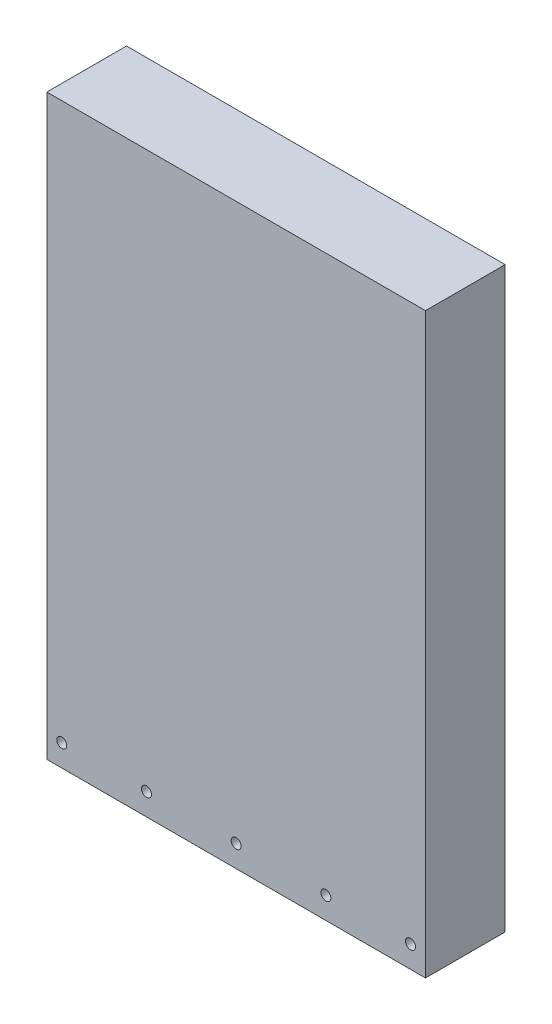
SolidWorks part; units mm, degrees
ref_plane "Plano frontal" through (0, 0, 0) normal (0, 0, 1) x (1, 0, 0)
ref_plane "Plano superior" through (0, 0, 0) normal (0, 1, 0) x (1, 0, 0)
ref_plane "Plano direito" through (0, 0, 0) normal (1, 0, 0) x (0, 0, -1)
sketch "Esboço1" plane through (0, 0, 0) normal (0, 0, 1) x (1, 0, 0)
  line L1 (0, 0) -> (190, 0)
  line L2 (0, 0) -> (0, 290)
  line L3 (0, 290) -> (190, 290)
  line L4 (190, 0) -> (190, 290)
  line L5 (5, 285) -> (185, 285)
  line L6 (5, 285) -> (5, 5)
  line L7 (5, 5) -> (185, 5)
  line L8 (185, 285) -> (185, 5)
  point P11 (-15.4865, 377.0233)
  dimension "D1" = 290
  dimension "D2" = 190
  dimension "D3" = 5
  dimension "D4" = 5
  dimension "D5" = 5
  dimension "D6" = 5
extrude "Ressalto-extrusão1" add sketch "Esboço1" along normal blind 40
sketch "Esboço2" plane through (0, 0, 40) normal (0, 0, 1) x (1, 0, 0)
  line L1 (5, 285) -> (185, 285)
  line L2 (5, 285) -> (5, 5)
  line L3 (5, 5) -> (185, 5)
  line L4 (185, 285) -> (185, 5)
extrude "Ressalto-extrusão2" add sketch "Esboço2" against normal blind 25
sketch "Esboço4" plane through (0, 0, 15) normal (0, 0, -1) x (-1, 0, 0)
  line L0 (-5, 5) -> (-185, 5) construction
  line L1 (-185, 5) -> (-175, 5)
  line L2 (-185, 5) -> (-185, 35)
  line L4 (-175, 5) -> (-175, 34.1716)
  line L6 (-150, 34.1716) -> (-150, 5)
  line L7 (-150, 5) -> (-130, 5)
  line L8 (-130, 34.1716) -> (-130, 5)
  line L9 (-5, 5) -> (-185, 5) construction
  line L11 (-105, 34.1716) -> (-105, 5)
  line L12 (-105, 5) -> (-85, 5)
  line L13 (-85, 34.1716) -> (-85, 5)
  line L15 (-60, 34.1716) -> (-60, 5)
  line L16 (-60, 5) -> (-40, 5)
  line L17 (-40, 34.1716) -> (-40, 5)
  line L18 (-5, 285) -> (-5, 5) construction
  line L20 (-5, 35) -> (-5, 5)
  line L21 (-5, 5) -> (-15, 5)
  line L22 (-15, 34.1716) -> (-15, 5)
  line L23 (-185, 35) -> (-185, 45)
  line L24 (-185, 5) -> (-185, 285) construction
  line L25 (-185, 45) -> (-175.5858, 35.5858)
  line L26 (-149.4142, 35.5858) -> (-141.4142, 43.5858)
  line L27 (-138.5858, 43.5858) -> (-130.5858, 35.5858)
  line L28 (-104.4142, 35.5858) -> (-96.4142, 43.5858)
  line L29 (-93.5858, 43.5858) -> (-85.5858, 35.5858)
  line L30 (-59.4142, 35.5858) -> (-51.4142, 43.5858)
  line L31 (-48.5858, 43.5858) -> (-40.5858, 35.5858)
  line L32 (-14.4142, 35.5858) -> (-5, 45)
  line L33 (-5, 45) -> (-5, 35)
  arc A0 (-175.5858, 35.5858) -> (-175, 34.1716) centre (-177, 34.1716) cw
  arc A1 (-149.4142, 35.5858) -> (-150, 34.1716) centre (-148, 34.1716) ccw
  arc A2 (-130.5858, 35.5858) -> (-130, 34.1716) centre (-132, 34.1716) cw
  arc A3 (-104.4142, 35.5858) -> (-105, 34.1716) centre (-103, 34.1716) ccw
  arc A4 (-85.5858, 35.5858) -> (-85, 34.1716) centre (-87, 34.1716) cw
  arc A5 (-59.4142, 35.5858) -> (-60, 34.1716) centre (-58, 34.1716) ccw
  arc A6 (-40.5858, 35.5858) -> (-40, 34.1716) centre (-42, 34.1716) cw
  arc A7 (-14.4142, 35.5858) -> (-15, 34.1716) centre (-13, 34.1716) ccw
  arc A8 (-51.4142, 43.5858) -> (-48.5858, 43.5858) centre (-50, 42.1716) cw
  arc A9 (-96.4142, 43.5858) -> (-93.5858, 43.5858) centre (-95, 42.1716) cw
  arc A10 (-141.4142, 43.5858) -> (-138.5858, 43.5858) centre (-140, 42.1716) cw
  point P27 (-140, 5)
  point P35 (-95, 5)
  point P36 (-50, 5)
  point P39 (-175, 35)
  point P42 (-150, 35)
  point P45 (-130, 35)
  point P48 (-105, 35)
  point P53 (-60, 35)
  point P58 (-15, 35)
  point P61 (-50, 45)
  point P64 (-95, 45)
  point P67 (-140, 45)
  dimension "D7" = 2
  dimension "D2" = 10
  dimension "D3" = 25
  dimension "D4" = 25
  dimension "D5" = 25
  dimension "D6" = 25
  dimension "D8" = 30
  dimension "D9" = 30
  dimension "D10" = 30
  dimension "D11" = 10
  dimension "D12" = 10
  dimension "D13" = 10
  dimension "D14" = 10
  dimension "D15" = 10
  dimension "D16" = 20
  dimension "D17" = 20
  dimension "D18" = 20
  dimension "D19" = 10
  dimension "D20" = 40
extrude "Ressalto-extrusão3" add sketch "Esboço4" along normal blind 15
sketch "Esboço5" plane through (0, 0, 0) normal (0, 0, -1) x (-1, 0, 0)
  line L0 (-185, 180) -> (-5, 180) construction
  line L1 (-185, 45) -> (-185, 285) construction
  line L2 (-5, 285) -> (-5, 45) construction
  line L3 (-185, 60) -> (-5, 60) construction
  line L4 (-185, 165) -> (-5, 165) construction
  line L5 (-5, 150) -> (-185, 150) construction
  line L6 (-185, 135) -> (-5, 135) construction
  line L7 (-185, 45) -> (-185, 285) construction
  line L8 (-5, 120) -> (-185.0319, 120) construction
  line L9 (-185, 105) -> (-5, 105) construction
  line L10 (-5, 90) -> (-185, 90) construction
  line L11 (-185, 75) -> (-5, 75) construction
  line L12 (-185, 195) -> (-5, 195) construction
  line L13 (-5, 210) -> (-185, 210) construction
  line L14 (-185, 225) -> (-5, 225) construction
  line L15 (-185, 240) -> (-5, 240) construction
  line L16 (-5, 255) -> (-185, 255) construction
  line L17 (-185, 270) -> (-5, 270) construction
  line L18 (-95, 270) -> (-95, 60) construction
  line L19 (-77, 60) -> (-77, 270) construction
  line L20 (-59, 270) -> (-59, 60) construction
  line L21 (-41, 270) -> (-41, 60) construction
  line L22 (-23, 270) -> (-23, 60) construction
  line L23 (-113, 60) -> (-113, 270) construction
  line L24 (-131, 270) -> (-131, 60) construction
  line L25 (-149, 60) -> (-149, 270) construction
  line L26 (-167, 270) -> (-167, 60) construction
  circle A0 centre (-167, 270) radius 0.75
  circle A1 centre (-131, 270) radius 0.75
  circle A2 centre (-95, 270) radius 0.75
  circle A3 centre (-59, 270) radius 0.75
  circle A4 centre (-23, 270) radius 0.75
  circle A5 centre (-41, 255) radius 0.75
  circle A6 centre (-77, 255) radius 0.75
  circle A7 centre (-113, 255) radius 0.75
  circle A8 centre (-149, 255) radius 0.75
  circle A9 centre (-167, 240) radius 0.75
  circle A10 centre (-131, 240) radius 0.75
  circle A11 centre (-95, 240) radius 0.75
  circle A12 centre (-59, 240) radius 0.75
  circle A13 centre (-23, 240) radius 0.75
  circle A14 centre (-149, 225) radius 0.75
  circle A15 centre (-113, 225) radius 0.75
  circle A16 centre (-77, 225) radius 0.75
  circle A17 centre (-41, 225) radius 0.75
  circle A18 centre (-167, 210) radius 0.75
  circle A19 centre (-131, 210) radius 0.75
  circle A20 centre (-95, 210) radius 0.75
  circle A21 centre (-59, 210) radius 0.75
  circle A22 centre (-23, 210) radius 0.75
  circle A23 centre (-149, 195) radius 0.75
  circle A24 centre (-113, 195) radius 0.75
  circle A25 centre (-77, 195) radius 0.75
  circle A26 centre (-41, 195) radius 0.75
  circle A28 centre (-23, 180) radius 0.75
  circle A29 centre (-59, 180) radius 0.75
  circle A30 centre (-95, 180) radius 0.75
  circle A31 centre (-131, 180) radius 0.75
  circle A32 centre (-167, 180) radius 0.75
  circle A33 centre (-149, 165) radius 0.75
  circle A34 centre (-113, 165) radius 0.75
  circle A35 centre (-77, 165) radius 0.75
  circle A36 centre (-41, 165) radius 0.75
  circle A38 centre (-23, 150) radius 0.75
  circle A39 centre (-59, 150) radius 0.75
  circle A40 centre (-95, 150) radius 0.75
  circle A41 centre (-131, 150) radius 0.75
  circle A43 centre (-167, 150) radius 0.75
  circle A44 centre (-149, 135) radius 0.75
  circle A45 centre (-113, 135) radius 0.75
  circle A46 centre (-77, 135) radius 0.75
  circle A47 centre (-41, 135) radius 0.75
  circle A48 centre (-167, 120) radius 0.75
  circle A49 centre (-131, 120) radius 0.75
  circle A50 centre (-95.0159, 120) radius 0.75
  circle A51 centre (-59, 120) radius 0.75
  circle A52 centre (-23, 120) radius 0.75
  circle A53 centre (-41, 105) radius 0.75
  circle A54 centre (-77, 105) radius 0.75
  circle A55 centre (-113, 105) radius 0.75
  circle A56 centre (-149, 105) radius 0.75
  circle A57 centre (-167, 90) radius 0.75
  circle A58 centre (-149, 75) radius 0.75
  circle A59 centre (-131, 90) radius 0.75
  circle A60 centre (-113, 75) radius 0.75
  circle A61 centre (-95, 90) radius 0.75
  circle A62 centre (-77, 75) radius 0.75
  circle A63 centre (-59, 90) radius 0.75
  circle A64 centre (-41, 75) radius 0.75
  circle A65 centre (-23, 90) radius 0.75
  circle A66 centre (-23, 60) radius 0.75
  circle A68 centre (-59, 60) radius 0.75
  circle A69 centre (-95, 60) radius 0.75
  circle A70 centre (-131, 60) radius 0.75
  circle A71 centre (-167, 60) radius 0.75
  dimension "D25" = 1.5
  dimension "D1" = 15
  dimension "D2" = 15
  dimension "D3" = 15
  dimension "D4" = 15
  dimension "D5" = 15
  dimension "D6" = 15
  dimension "D7" = 15
  dimension "D8" = 15
  dimension "D9" = 15
  dimension "D10" = 15
  dimension "D11" = 15
  dimension "D12" = 15
  dimension "D13" = 15
  dimension "D14" = 15
  dimension "D15" = 15
  dimension "D16" = 18
  dimension "D17" = 18
  dimension "D18" = 18
  dimension "D19" = 18
  dimension "D20" = 18
  dimension "D21" = 18
  dimension "D22" = 18
  dimension "D23" = 18
  dimension "D24" = 18
extrude "Ressalto-extrusão5" add sketch "Esboço5" against normal blind 15
sketch "Esboço7" plane through (0, 0, 0) normal (0, 0, -1) x (-1, 0, 0)
  circle A0 centre (-167, 270) radius 1.25
  circle A1 centre (-149, 255) radius 1.25
  circle A2 centre (-131, 270) radius 1.25
  circle A3 centre (-113, 255) radius 1.25
  circle A4 centre (-95, 270) radius 1.25
  circle A5 centre (-59, 270) radius 1.25
  circle A6 centre (-23, 270) radius 1.25
  circle A7 centre (-77, 255) radius 1.25
  circle A8 centre (-41, 255) radius 1.25
  circle A9 centre (-23, 240) radius 1.25
  circle A10 centre (-59, 240) radius 1.25
  circle A11 centre (-77, 225) radius 1.25
  circle A12 centre (-41, 225) radius 1.25
  circle A13 centre (-95, 240) radius 1.25
  circle A14 centre (-113, 225) radius 1.25
  circle A15 centre (-167, 240) radius 1.25
  circle A16 centre (-149, 225) radius 1.25
  circle A17 centre (-131, 240) radius 1.25
  circle A18 centre (-131, 210) radius 1.25
  circle A19 centre (-167, 210) radius 1.25
  circle A20 centre (-149, 195) radius 1.25
  circle A21 centre (-167, 180) radius 1.25
  circle A22 centre (-131, 180) radius 1.25
  circle A23 centre (-113, 195) radius 1.25
  circle A24 centre (-95, 210) radius 1.25
  circle A25 centre (-77, 195) radius 1.25
  circle A26 centre (-95, 180) radius 1.25
  circle A27 centre (-77, 165) radius 1.25
  circle A28 centre (-59, 180) radius 1.25
  circle A29 centre (-59, 210) radius 1.25
  circle A30 centre (-23, 210) radius 1.25
  circle A31 centre (-41, 195) radius 1.25
  circle A32 centre (-23, 180) radius 1.25
  circle A33 centre (-41, 165) radius 1.25
  circle A34 centre (-23, 150) radius 1.25
  circle A35 centre (-41, 135) radius 1.25
  circle A36 centre (-59, 150) radius 1.25
  circle A37 centre (-23, 120) radius 1.25
  circle A38 centre (-59, 120) radius 1.25
  circle A39 centre (-113, 165) radius 1.25
  circle A40 centre (-149, 165) radius 1.25
  circle A41 centre (-131, 150) radius 1.25
  circle A42 centre (-167, 150) radius 1.25
  circle A43 centre (-149, 135) radius 1.25
  circle A44 centre (-113, 135) radius 1.25
  circle A45 centre (-95, 150) radius 1.25
  circle A46 centre (-95.0159, 120) radius 1.25
  circle A47 centre (-77, 135) radius 1.25
  circle A48 centre (-167, 120) radius 1.25
  circle A49 centre (-149, 105) radius 1.25
  circle A50 centre (-131, 120) radius 1.25
  circle A51 centre (-167, 90) radius 1.25
  circle A52 centre (-131, 90) radius 1.25
  circle A53 centre (-95, 90) radius 1.25
  circle A54 centre (-113, 105) radius 1.25
  circle A55 centre (-59, 90) radius 1.25
  circle A56 centre (-77, 105) radius 1.25
  circle A57 centre (-41, 105) radius 1.25
  circle A58 centre (-23, 90) radius 1.25
  circle A59 centre (-41, 75) radius 1.25
  circle A60 centre (-77, 75) radius 1.25
  circle A61 centre (-23, 60) radius 1.25
  circle A62 centre (-59, 60) radius 1.25
  circle A63 centre (-167, 60) radius 1.25
  circle A64 centre (-149, 75) radius 1.25
  circle A65 centre (-131, 60) radius 1.25
  circle A66 centre (-113, 75) radius 1.25
  circle A67 centre (-95, 60) radius 1.25
  dimension "D1" = 2.5
extrude "Ressalto-extrusão6" add sketch "Esboço7" against normal blind 1
sketch "Esboço8" plane through (0, 0, 15) normal (0, 0, -1) x (-1, 0, 0)
  line L0 (-185, 195) -> (-175, 195)
  line L1 (-185, 45) -> (-185, 285) construction
  line L2 (-175, 195) -> (-185, 210)
  line L3 (-185, 210) -> (-185, 195)
  line L5 (-185, 105) -> (-175, 105)
  line L6 (-175, 105) -> (-185, 120)
  line L7 (-185, 120) -> (-185, 105)
  line L8 (-5, 105) -> (-15, 105)
  line L9 (-5, 285) -> (-5, 45) construction
  line L10 (-15, 105) -> (-5, 120)
  line L11 (-5, 120) -> (-5, 105)
  line L12 (-5, 195) -> (-15, 195)
  line L13 (-15, 195) -> (-5, 210)
  line L14 (-5, 210) -> (-5, 195)
  circle A0 centre (-167, 90) radius 1.25 construction
  circle A2 centre (-167, 180) radius 1.25 construction
  dimension "D1" = 10
  dimension "D2" = 15
  dimension "D3" = 15
  dimension "D5" = 15
extrude "Ressalto-extrusão7" add sketch "Esboço8" along normal blind 15
fillet "Filete1" radius 1 4 edges at (15, 195, 7.5) (15, 105, 7.5) (175, 105, 7.5) (175, 195, 7.5)
sketch "Esboço11" plane through (150, 0, 0) normal (1, 0, 0) x (0, 0, -1)
  line L0 (0, 5) -> (-15, 5) construction
  line L1 (0, 34.1716) -> (0, 5) construction
  circle A0 centre (-8, 11) radius 2.5
  dimension "D1" = 5
  dimension "D2" = 6
  dimension "D3" = 8
extrude "Corte-extrusão1" cut sketch "Esboço11" against normal blind 120
sketch "Esboço12" plane through (175, 0, 0) normal (-1, 0, 0) x (0, 0, 1)
  line L0 (0, 5) -> (0, 34.1716) construction
  line L2 (0, 5) -> (15, 5) construction
  circle A0 centre (8, 11) radius 2.5
  dimension "D1" = 5
  dimension "D2" = 8
  dimension "D3" = 6
extrude "Corte-extrusão2" cut sketch "Esboço12" against normal blind 10
sketch "Esboço13" plane through (15, 0, 0) normal (1, 0, 0) x (0, 0, -1)
  line L0 (0, 5) -> (-15, 5) construction
  line L1 (0, 34.1716) -> (0, 5) construction
  circle A0 centre (-8, 11) radius 2.5
  dimension "D1" = 5
  dimension "D2" = 6
  dimension "D3" = 8
extrude "Corte-extrusão3" cut sketch "Esboço13" against normal blind 10
sketch "Esboço14" plane through (0, 0, 40) normal (0, 0, 1) x (1, 0, 0)
  line L1 (0, 290) -> (0, 0) construction
  line L2 (0, 0) -> (190, 0) construction
  line L3 (190, 0) -> (190, 290) construction
  circle A0 centre (7.5, 11) radius 2.5
  circle A1 centre (50, 11) radius 2.5
  circle A2 centre (95, 11) radius 2.5
  circle A3 centre (140, 11) radius 2.5
  circle A4 centre (182.5, 11) radius 2.5
  dimension "D1" = 5
  dimension "D2" = 5
  dimension "D3" = 11
  dimension "D4" = 5
  dimension "D5" = 11
  dimension "D6" = 45
  dimension "D7" = 45
  dimension "D8" = 95
extrude "Corte-extrusão4" cut sketch "Esboço14" against normal blind 26
